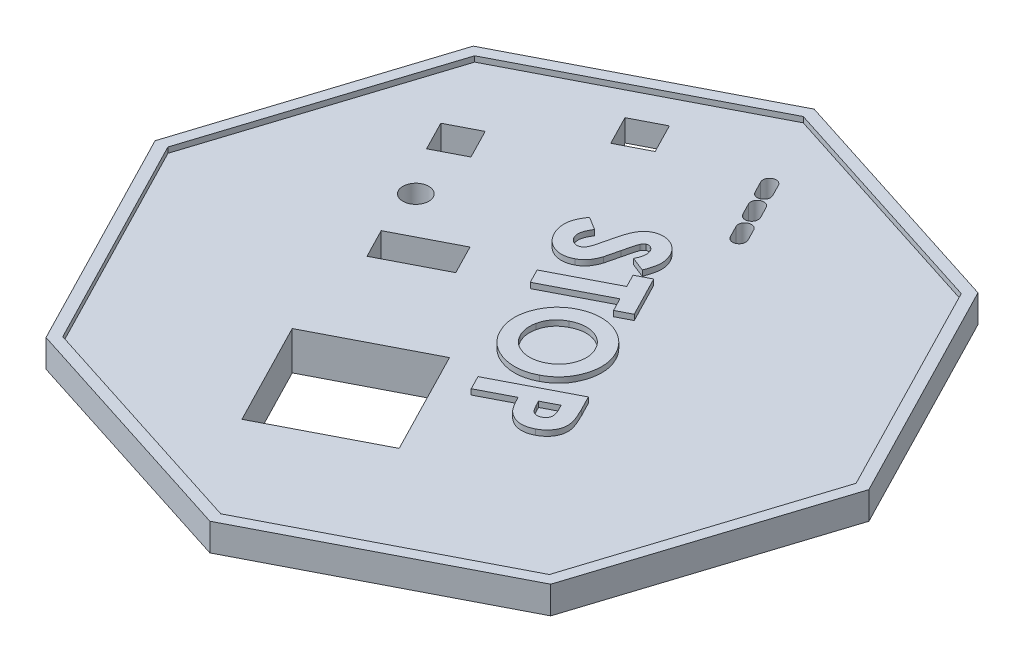
SolidWorks part; units mm, degrees
ref_plane "Front Plane" through (0, 0, 0) normal (0, 0, 1) x (1, 0, 0)
ref_plane "Top Plane" through (0, 0, 0) normal (0, 1, 0) x (1, 0, 0)
ref_plane "Right Plane" through (0, 0, 0) normal (1, 0, 0) x (0, 0, -1)
sketch "Sketch2" plane through (0, 0, 0) normal (0, 1, 0) x (1, 0, 0)
  line L1 (76.2, 6.3352) -> (49.4019, 58.3612)
  line L2 (49.4019, 58.3612) -> (-6.3352, 76.2)
  line L3 (-6.3352, 76.2) -> (-58.3612, 49.4019)
  line L4 (-58.3612, 49.4019) -> (-76.2, -6.3352)
  line L5 (-76.2, -6.3352) -> (-49.4019, -58.3612)
  line L6 (-49.4019, -58.3612) -> (6.3352, -76.2)
  line L7 (6.3352, -76.2) -> (58.3612, -49.4019)
  line L8 (58.3612, -49.4019) -> (76.2, 6.3352)
  circle A0 centre (0, 0) radius 70.6425 construction
  dimension "D1" = 152.4
extrude "Boss-Extrude6" add sketch "Sketch2" along normal blind 6.35
sketch "Sketch3" plane through (0, 0, 0) normal (0, -1, 0) x (1, 0, 0)
  line L16 (65.2407, -5.424) -> (49.9675, 42.2968)
  line L17 (49.9675, 42.2968) -> (5.424, 65.2407)
  line L18 (5.424, 65.2407) -> (-42.2968, 49.9675)
  line L19 (-42.2968, 49.9675) -> (-65.2407, 5.424)
  line L20 (-65.2407, 5.424) -> (-49.9675, -42.2968)
  line L21 (-49.9675, -42.2968) -> (-5.424, -65.2407)
  line L22 (-5.424, -65.2407) -> (42.2968, -49.9675)
  line L23 (42.2968, -49.9675) -> (65.2407, -5.424)
  line L24 (65.2407, -5.424) -> (49.9675, 42.2968)
  line L25 (49.9675, 42.2968) -> (5.424, 65.2407)
  line L26 (5.424, 65.2407) -> (-42.2968, 49.9675)
  line L27 (-42.2968, 49.9675) -> (-65.2407, 5.424)
  line L28 (-65.2407, 5.424) -> (-49.9675, -42.2968)
  line L29 (-49.9675, -42.2968) -> (-5.424, -65.2407)
  line L30 (-5.424, -65.2407) -> (42.2968, -49.9675)
  line L31 (42.2968, -49.9675) -> (65.2407, -5.424)
  dimension "D1" = 10.16
extrude "Boss-Extrude7" add sketch "Sketch3" along normal blind 3.81
sketch "Sketch4" plane through (0, 6.35, 0) normal (0, 1, 0) x (1, 0, 0)
  line L16 (56.2628, -47.6256) -> (73.4602, 6.1074)
  line L17 (73.4602, 6.1074) -> (47.6256, 56.2628)
  line L18 (47.6256, 56.2628) -> (-6.1074, 73.4602)
  line L19 (-6.1074, 73.4602) -> (-56.2628, 47.6256)
  line L20 (-56.2628, 47.6256) -> (-73.4602, -6.1074)
  line L21 (-73.4602, -6.1074) -> (-47.6256, -56.2628)
  line L22 (-47.6256, -56.2628) -> (6.1074, -73.4602)
  line L23 (6.1074, -73.4602) -> (56.2628, -47.6256)
  line L24 (56.2628, -47.6256) -> (73.4602, 6.1074)
  line L25 (73.4602, 6.1074) -> (47.6256, 56.2628)
  line L26 (47.6256, 56.2628) -> (-6.1074, 73.4602)
  line L27 (-6.1074, 73.4602) -> (-56.2628, 47.6256)
  line L28 (-56.2628, 47.6256) -> (-73.4602, -6.1074)
  line L29 (-73.4602, -6.1074) -> (-47.6256, -56.2628)
  line L30 (-47.6256, -56.2628) -> (6.1074, -73.4602)
  line L31 (6.1074, -73.4602) -> (56.2628, -47.6256)
  dimension "D1" = 2.54
extrude "Cut-Extrude1" cut sketch "Sketch4" against normal blind 1.27
sketch "Sketch5" plane through (0, 5.08, 0) normal (0, 1, 0) x (1, 0, 0)
  line L0 (-32.3482, 62.8009) -> (32.3482, -62.8009) construction
  line L1 (-6.3352, 76.2) -> (-58.3612, 49.4019) construction
  line L2 (6.3352, -76.2) -> (58.3612, -49.4019) construction
  text T0 "STOP" font "Century Gothic" height in points 72
extrude "Boss-Extrude8" add sketch "Sketch5" along normal blind 1.27
sketch "Sketch10" plane through (0, 5.08, 0) normal (0, 1, 0) x (1, 0, 0)
  line L0 (-31.1851, 60.5429) -> (31.1851, -60.5429) construction
  line L1 (-6.1074, 73.4602) -> (-56.2628, 47.6256) construction
  line L2 (6.1074, -73.4602) -> (56.2628, -47.6256) construction
  line L3 (60.5429, 31.1851) -> (-60.5429, -31.1851) construction
  line L4 (73.4602, 6.1074) -> (47.6256, 56.2628) construction
  line L5 (-73.4602, -6.1074) -> (-47.6256, -56.2628) construction
  line L6 (0, -14.4539) -> (12.3637, -38.4568)
  line L7 (0, -14.4539) -> (-24.0029, -26.8176)
  line L8 (12.3637, -38.4568) -> (-11.6392, -50.8205)
  line L9 (-24.0029, -26.8176) -> (-11.6392, -50.8205)
  dimension "D1" = 27
  dimension "D2" = 27
extrude "Cut-Extrude3" cut sketch "Sketch10" against normal through all
sketch "Sketch11" plane through (0, 6.35, 0) normal (0, 1, 0) x (1, 0, 0)
  line L0 (56.2628, -47.6256) -> (-6.1074, 73.4602) construction
  line L1 (9.634, 42.8997) -> (8.2383, 45.6094) construction
  line L2 (8.2792, 42.2019) -> (6.8834, 44.9115)
  line L3 (10.9888, 43.5976) -> (9.5931, 46.3073)
  line L4 (6.5692, 48.8497) -> (5.1735, 51.5593) construction
  line L5 (5.2144, 48.1518) -> (3.8187, 50.8615)
  line L6 (7.9241, 49.5475) -> (6.5283, 52.2572)
  line L7 (3.5658, 54.6805) -> (2.1701, 57.3902) construction
  line L8 (2.211, 53.9827) -> (0.8153, 56.6923)
  line L9 (4.9207, 55.3784) -> (3.5249, 58.088)
  arc A0 (8.2792, 42.2019) -> (10.9888, 43.5976) centre (9.634, 42.8997) ccw
  arc A1 (9.5931, 46.3073) -> (6.8834, 44.9115) centre (8.2383, 45.6094) ccw
  arc A2 (5.2144, 48.1518) -> (7.9241, 49.5475) centre (6.5692, 48.8497) ccw
  arc A3 (6.5283, 52.2572) -> (3.8187, 50.8615) centre (5.1735, 51.5593) ccw
  arc A4 (2.211, 53.9827) -> (4.9207, 55.3784) centre (3.5658, 54.6805) ccw
  arc A5 (3.5249, 58.088) -> (0.8153, 56.6923) centre (2.1701, 57.3902) ccw
  point P6 (8.9361, 44.2546)
  point P11 (5.8714, 50.2045)
  point P20 (2.868, 56.0354)
extrude "Cut-Extrude4" cut sketch "Sketch11" against normal through all contours L6 A3 L5 A2 | L9 A5 L8 A4 | L3 A1 L2 A0
sketch "Sketch13" plane through (0, 5.08, 0) normal (0, 1, 0) x (1, 0, 0)
  circle A0 centre (-36.6985, 14.4539) radius 3
  dimension "10mm" = 6
extrude "Cut-Extrude5" cut sketch "Sketch13" against normal through all
sketch "Sketch16" plane through (0, 5.08, 0) normal (0, 1, 0) x (1, 0, 0)
  line L0 (-56.2628, 47.6256) -> (6.1074, -73.4602) construction
  line L1 (-33.3138, 3.0723) -> (-29.8245, -3.7019)
  line L2 (-33.3138, 3.0723) -> (-19.7655, 10.0509)
  line L3 (-29.8245, -3.7019) -> (-16.2762, 3.2767)
  line L4 (-19.7655, 10.0509) -> (-16.2762, 3.2767)
  dimension "D1" = 7.62
  dimension "D2" = 15.24
extrude "Cut-Extrude6" cut sketch "Sketch16" against normal through all
sketch "Sketch18" plane through (0, 5.08, 0) normal (0, 1, 0) x (1, 0, 0)
  line L0 (-56.2628, 47.6256) -> (6.1074, -73.4602) construction
  line L1 (-47.9459, 31.4791) -> (-44.4566, 24.7049)
  line L2 (-47.9459, 31.4791) -> (-41.1717, 34.9684)
  line L3 (-44.4566, 24.7049) -> (-37.6824, 28.1943)
  line L4 (-41.1717, 34.9684) -> (-37.6824, 28.1943)
  dimension "D1" = 7.62
  dimension "D2" = 7.62
extrude "Cut-Extrude7" cut sketch "Sketch18" against normal through all
sketch "Sketch19" plane through (0, 5.08, 0) normal (0, 1, 0) x (1, 0, 0)
  line L0 (-31.1851, 60.5429) -> (31.1851, -60.5429) construction
  line L1 (-6.1074, 73.4602) -> (-56.2628, 47.6256) construction
  line L2 (6.1074, -73.4602) -> (56.2628, -47.6256) construction
  line L3 (-27.7549, 53.8835) -> (-24.2656, 47.1093)
  line L4 (-27.7549, 53.8835) -> (-20.9807, 57.3728)
  line L5 (-24.2656, 47.1093) -> (-17.4914, 50.5986)
  line L6 (-20.9807, 57.3728) -> (-17.4914, 50.5986)
  dimension "D1" = 7.62
  dimension "D2" = 7.62
extrude "Cut-Extrude8" cut sketch "Sketch19" against normal through all
